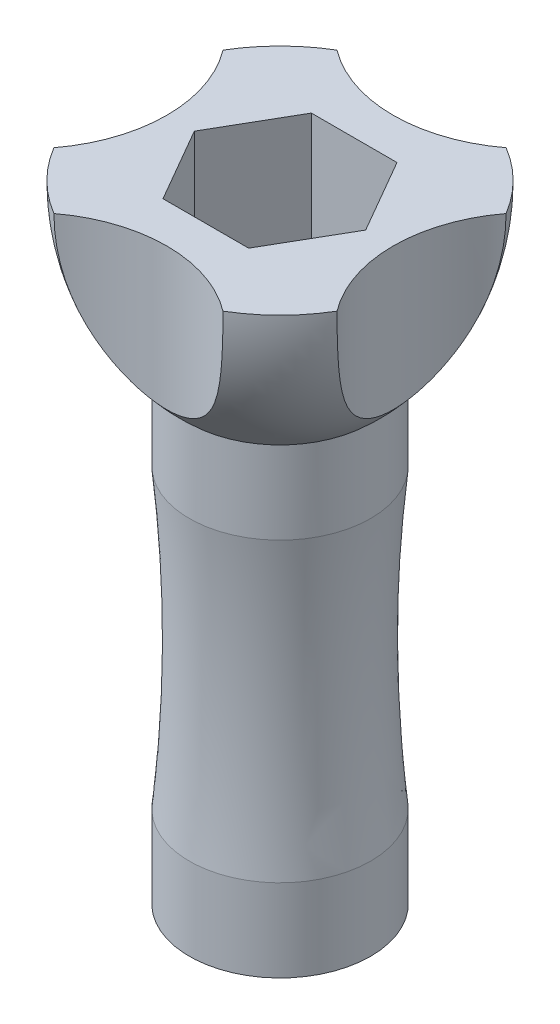
SolidWorks part; units mm, degrees
ref_plane "Front Plane" through (0, 0, 0) normal (0, 0, 1) x (1, 0, 0)
ref_plane "Top Plane" through (0, 0, 0) normal (0, 1, 0) x (1, 0, 0)
ref_plane "Right Plane" through (0, 0, 0) normal (1, 0, 0) x (0, 0, -1)
sketch "Sketch1" plane through (0, 0, 0) normal (0, 0, 1) x (1, 0, 0)
  line L0 (0, 81.0056) -> (0, -94.6003) construction
  line L1 (0, 81.0056) -> (-10, 81.0056)
  line L2 (-5.5, 71.0056) -> (-5.5, 66.0056)
  line L3 (-5.5, 48.0056) -> (-5.5, 43.0056)
  line L4 (-5.5, 43.0056) -> (0, 43.0056)
  line L5 (0, 81.0056) -> (0, 43.0056)
  arc A0 (-10, 81.0056) -> (-5.5, 71.0056) centre (3.3611, 81.0056) ccw
  spline S0 degree 2 poles (-5.5, 66.0056) (-4.5877, 56.9984) (-5.5, 48.0056) knots 0 0 0 1 1 1
  dimension "D1" = 20
  dimension "D2" = 10
  dimension "D3" = 5
  dimension "D4" = 18
  dimension "D5" = 5
  dimension "D6" = 11
  dimension "D7" = 11
revolve "Revolve3" add sketch "Sketch1" angle 360 about L0
sketch "Sketch2" plane through (0, 81.0056, 0) normal (0, 1, 0) x (1, 0, 0)
  line L0 (0, 11.5031) -> (0, -11.9321) construction
  circle A0 centre (0, 15.3643) radius 8.5
  dimension "D1" = 17
extrude "Cut-Extrude1" cut sketch "Sketch2" against normal blind 10
pattern_circular "CirPattern1" count 4 over 360 about axis through (0, 0, 0) along (0, 1, 0) of "Cut-Extrude1"
ref_plane "Plane1" through (0, 81.0056, 0) normal (0, 1, 0) x (1, 0, 0)
sketch "Sketch3" plane through (0, 81.0056, 0) normal (0, 1, 0) x (1, 0, 0)
  line L1 (-2.5981, 4.5) -> (-5.1962, 0)
  line L2 (-5.1962, 0) -> (-2.5981, -4.5)
  line L3 (-2.5981, -4.5) -> (2.5981, -4.5)
  line L4 (2.5981, -4.5) -> (5.1962, 0)
  line L5 (5.1962, 0) -> (2.5981, 4.5)
  line L6 (2.5981, 4.5) -> (-2.5981, 4.5)
  circle A0 centre (0, 0) radius 4.5 construction
  dimension "D1" = 9
extrude "Cut-Extrude2" cut sketch "Sketch3" against normal blind 12
hole_wizard "Ø4.0 (4) Diameter Hole1" positions "Sketch5" profile "Sketch6" hole size "Ø4.0" standard "ANSI Metric" end condition through all
sketch "Sketch5" plane through (0, 69.0056, 0) normal (0, 1, 0) x (1, 0, 0)
  point P0 (0, 0)
sketch "Sketch6" plane through (0, 69.0056, 0) normal (1, 0, 0) x (0, 0, 1)
  line L0 (0, 0) -> (0, 26)
  line L1 (0, 26) -> (2, 26)
  line L2 (2, 26) -> (2, 0)
  line L5 (2, 0) -> (0, 0)
  line L11 (0, -6.35) -> (0, 107.95) construction
  dimension "Thru Hole Dia." = 4
  dimension "Thru Hole Depth" = 26
